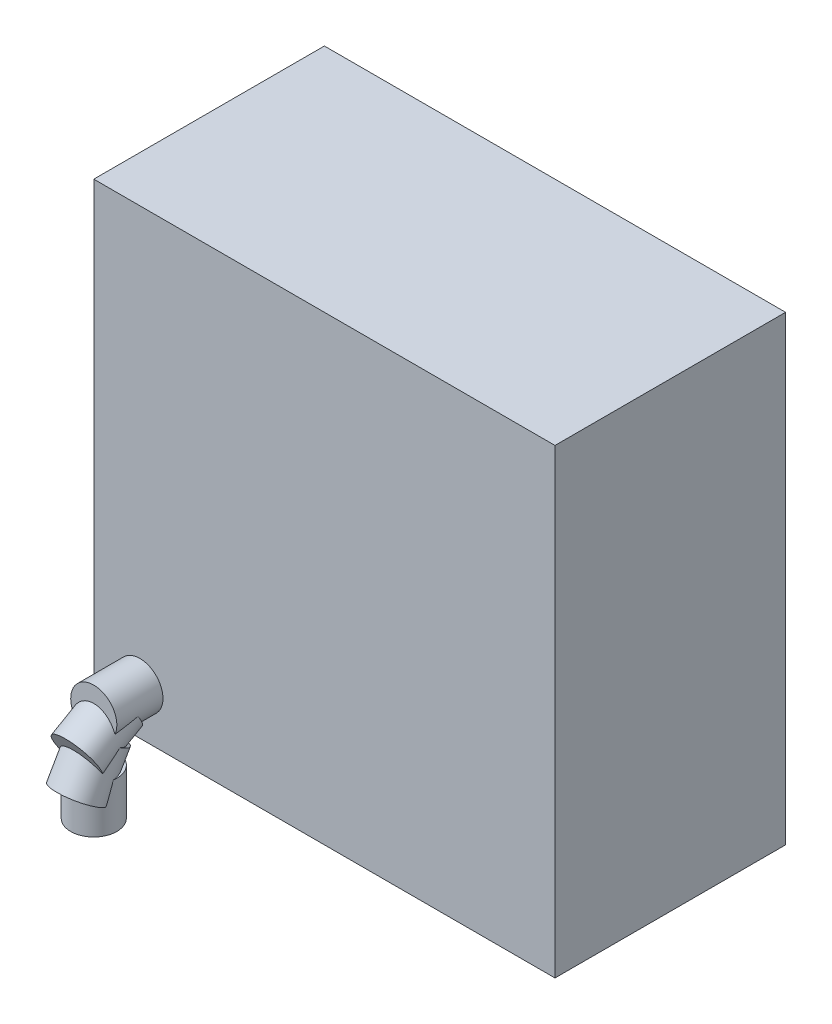
SolidWorks part; units mm, degrees
ref_plane "前视基准面" through (0, 0, 0) normal (0, 0, 1) x (1, 0, 0)
ref_plane "上视基准面" through (0, 0, 0) normal (0, 1, 0) x (1, 0, 0)
ref_plane "右视基准面" through (0, 0, 0) normal (1, 0, 0) x (0, 0, -1)
other "Configuration Table"
sketch "草图1" plane through (0, 0, 0) normal (0, 0, 1) x (1, 0, 0)
  line L1 (0, 0) -> (20, 0)
  line L2 (0, 0) -> (0, 20)
  line L3 (0, 20) -> (20, 20)
  line L4 (20, 0) -> (20, 20)
extrude "BaseBox" add sketch "草图1" along normal blind 10
sketch "草图2" plane through (0, 0, 10) normal (0, 0, 1) x (1, 0, 0)
  circle A0 centre (2, 2) radius 1
extrude "BossSeed" add sketch "草图2" along normal blind 2
pattern_circular "CircularPattern" count 4 every 30 about axis through (0, 0, 10) along (1, 0, 0) of "BossSeed"
